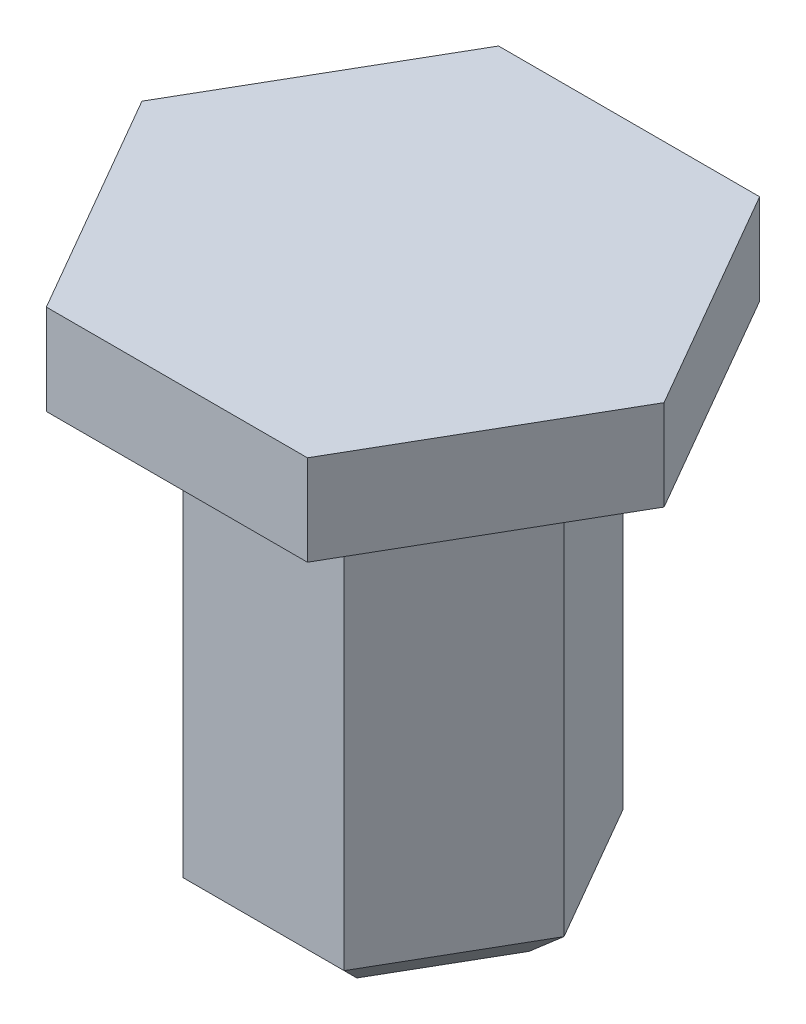
SolidWorks part; units mm, degrees
ref_plane "Front Plane" through (0, 0, 0) normal (0, 0, 1) x (1, 0, 0)
ref_plane "Top Plane" through (0, 0, 0) normal (0, 1, 0) x (1, 0, 0)
ref_plane "Right Plane" through (0, 0, 0) normal (1, 0, 0) x (0, 0, -1)
sketch "Sketch1" plane through (0, 0, 0) normal (0, 1, 0) x (1, 0, 0)
  line L1 (2.1362, 0) -> (1.0681, 1.85)
  line L2 (1.0681, 1.85) -> (-1.0681, 1.85)
  line L3 (-1.0681, 1.85) -> (-2.1362, 0)
  line L4 (-2.1362, 0) -> (-1.0681, -1.85)
  line L5 (-1.0681, -1.85) -> (1.0681, -1.85)
  line L6 (1.0681, -1.85) -> (2.1362, 0)
  circle A0 centre (0, 0) radius 1.85 construction
  dimension "D1" = 3.7
extrude "Boss-Extrude1" add sketch "Sketch1" along normal blind 6
sketch "Sketch2" plane through (0, 6, 0) normal (0, 1, 0) x (1, 0, 0)
  line L1 (3.4641, 0) -> (1.7321, 3)
  line L2 (1.7321, 3) -> (-1.7321, 3)
  line L3 (-1.7321, 3) -> (-3.4641, 0)
  line L4 (-3.4641, 0) -> (-1.7321, -3)
  line L5 (-1.7321, -3) -> (1.7321, -3)
  line L6 (1.7321, -3) -> (3.4641, 0)
  circle A0 centre (0, 0) radius 3 construction
  dimension "D1" = 6
extrude "Boss-Extrude2" add sketch "Sketch2" along normal blind 1.2
chamfer "Chamfer1" distance 0.4 angle 45 6 edges at (1.6021, 0, -0.925) (0, 0, -1.85) (-1.6021, 0, -0.925) (-1.6021, 0, 0.925) (0, 0, 1.85) (1.6021, 0, 0.925)
